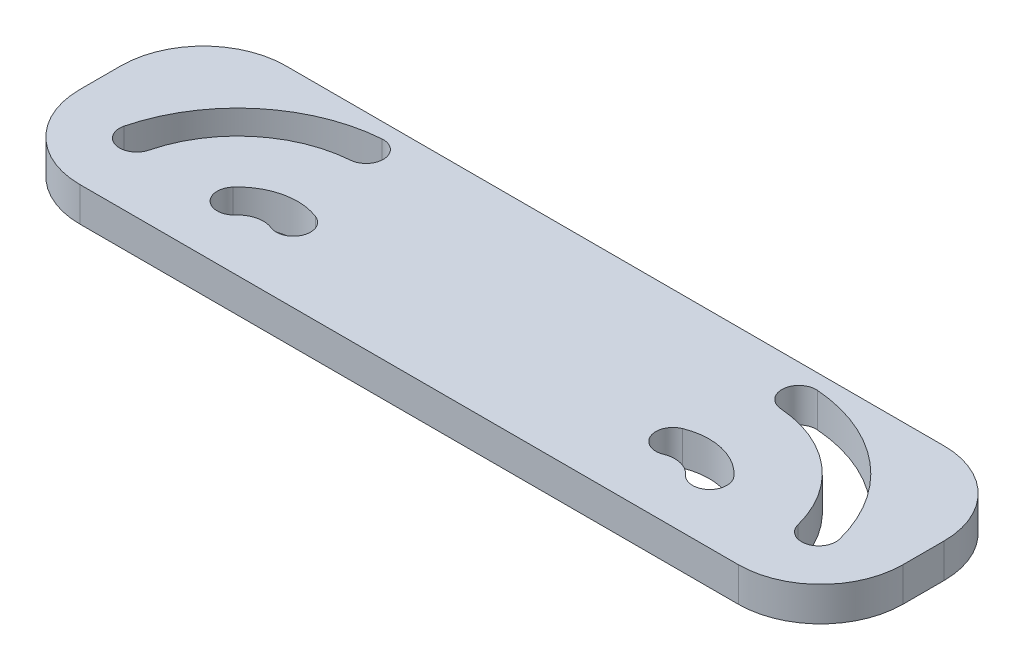
SolidWorks part; units mm, degrees
ref_plane "Front Plane" through (0, 0, 0) normal (0, 0, 1) x (1, 0, 0)
ref_plane "Top Plane" through (0, 0, 0) normal (0, 1, 0) x (1, 0, 0)
ref_plane "Right Plane" through (0, 0, 0) normal (1, 0, 0) x (0, 0, -1)
sketch "Sketch1" plane through (0, 0, 0) normal (0, 1, 0) x (1, 0, 0)
  line L5 (-38.1, 9.525) -> (38.1, 9.525)
  line L6 (-38.1, 9.525) -> (-38.1, -9.525)
  line L13 (-38.1, -9.525) -> (38.1, -9.525)
  line L14 (38.1, 9.525) -> (38.1, -9.525)
  line L15 (-38.1, 9.525) -> (38.1, -9.525) construction
  line L16 (-38.1, -9.525) -> (38.1, 9.525) construction
  point P0 (0, 0)
  dimension "D1" = 76.2
  dimension "D2" = 19.05
extrude "Boss-Extrude1" add sketch "Sketch1" along normal blind 3.175
sketch "Sketch6" plane through (0, 3.175, 0) normal (0, 1, 0) x (1, 0, 0)
  line L2 (-38.1, -9.525) -> (38.1, -9.525) construction
  line L3 (-38.1, 9.525) -> (-38.1, -9.525) construction
  line L4 (0, 9.525) -> (0, -11.9796) construction
  line L5 (38.1, 9.525) -> (-38.1, 9.525) construction
  arc A0 (-20.0369, 6.5336) -> (-31.5752, -3.175) centre (-19.05, -6.35) ccw construction
  arc A1 (-20.1581, 8.1164) -> (-33.114, -2.7849) centre (-19.05, -6.35) ccw
  arc A2 (-19.9156, 4.9507) -> (-30.0363, -3.5651) centre (-19.05, -6.35) ccw
  arc A3 (-19.9156, 4.9507) -> (-20.1581, 8.1164) centre (-20.0369, 6.5336) ccw
  arc A4 (-33.114, -2.7849) -> (-30.0363, -3.5651) centre (-31.5752, -3.175) ccw
  arc A5 (-17.5716, -2.6669) -> (-22.0054, -3.7011) centre (-19.05, -6.35) ccw construction
  arc A6 (-16.9803, -1.1936) -> (-23.1875, -2.6415) centre (-19.05, -6.35) ccw
  arc A7 (-18.163, -4.1401) -> (-20.8232, -4.7607) centre (-19.05, -6.35) ccw
  arc A8 (-18.163, -4.1401) -> (-16.9803, -1.1936) centre (-17.5716, -2.6669) ccw
  arc A9 (-23.1875, -2.6415) -> (-20.8232, -4.7607) centre (-22.0054, -3.7011) ccw
  arc A10 (17.5716, -2.6669) -> (22.0054, -3.7011) centre (19.05, -6.35) cw construction
  arc A11 (16.9803, -1.1936) -> (23.1875, -2.6415) centre (19.05, -6.35) cw
  arc A12 (18.163, -4.1401) -> (20.8232, -4.7607) centre (19.05, -6.35) cw
  arc A13 (18.163, -4.1401) -> (16.9803, -1.1936) centre (17.5716, -2.6669) cw
  arc A14 (23.1875, -2.6415) -> (20.8232, -4.7607) centre (22.0054, -3.7011) cw
  arc A15 (20.0369, 6.5336) -> (31.5752, -3.175) centre (19.05, -6.35) cw construction
  arc A16 (20.1581, 8.1164) -> (33.114, -2.7849) centre (19.05, -6.35) cw
  arc A17 (19.9156, 4.9507) -> (30.0363, -3.5651) centre (19.05, -6.35) cw
  arc A18 (19.9156, 4.9507) -> (20.1581, 8.1164) centre (20.0369, 6.5336) cw
  arc A19 (33.114, -2.7849) -> (30.0363, -3.5651) centre (31.5752, -3.175) cw
  point P4 (0, 0)
  point P5 (-27.3691, 3.537)
  point P10 (-19.9516, -2.485)
  point P27 (19.9516, -2.485)
  point P41 (27.3691, 3.537)
  dimension "D3" = 3.175
  dimension "D5" = 3.175
  dimension "D1" = 18.0631
  dimension "D2" = 16.0586
  dimension "D4" = 6.35
  dimension "D6" = 6.8581
  dimension "D7" = 20.5284
  dimension "D8" = 16.0946
  dimension "D9" = 3.175
  dimension "D10" = 19.05
extrude "Cut-Extrude1" cut sketch "Sketch6" against normal through all
fillet "Fillet1" radius 7.62 4 edges at (-38.1, 1.5875, -9.525) (38.1, 1.5875, -9.525) (38.1, 1.5875, 9.525) (-38.1, 1.5875, 9.525)
